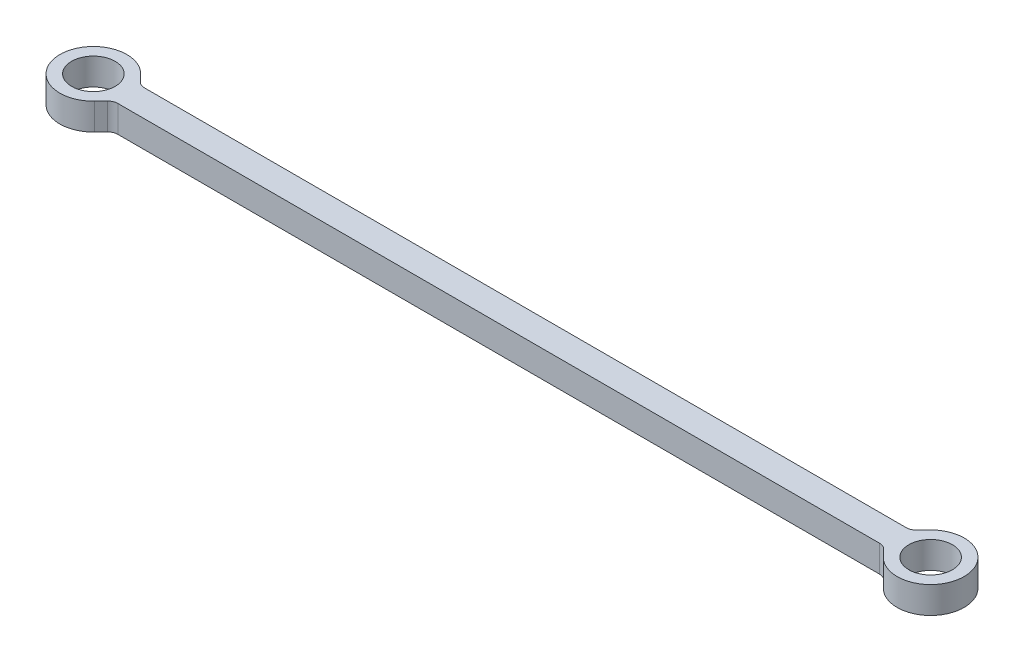
SolidWorks part; units mm, degrees
ref_plane "Спереди" through (0, 0, 0) normal (0, 0, 1) x (1, 0, 0)
ref_plane "Сверху" through (0, 0, 0) normal (0, 1, 0) x (1, 0, 0)
ref_plane "Справа" through (0, 0, 0) normal (1, 0, 0) x (0, 0, -1)
ref_plane "Плоскость4" through (0, 0, 0) normal (0, -1, 0) x (1, 0, 0)
sketch "Эскиз1" plane through (0, 0, 0) normal (0, -1, 0) x (1, 0, 0)
  line L0 (7.2414, -6.8966) -> (9.1133, -4.931)
  line L1 (11.2857, -4) -> (238.7143, -4)
  line L2 (240.8867, -4.931) -> (242.7586, -6.8966)
  line L3 (242.7586, 6.8966) -> (240.8867, 4.931)
  line L4 (238.7143, 4) -> (11.2857, 4)
  line L5 (9.1133, 4.931) -> (7.2414, 6.8966)
  circle A0 centre (0, 0) radius 6.5
  circle A1 centre (250, 0) radius 6.5
  arc A2 (7.2414, 6.8966) -> (7.2414, -6.8966) centre (0, 0) ccw
  arc A3 (9.1133, -4.931) -> (11.2857, -4) centre (11.2857, -7) cw
  arc A4 (238.7143, -4) -> (240.8867, -4.931) centre (238.7143, -7) cw
  arc A5 (242.7586, -6.8966) -> (242.7586, 6.8966) centre (250, 0) ccw
  arc A6 (240.8867, 4.931) -> (238.7143, 4) centre (238.7143, 7) cw
  arc A7 (11.2857, 4) -> (9.1133, 4.931) centre (11.2857, 7) cw
extrude "Бобышка-Вытянуть1" add sketch "Эскиз1" against normal blind 8
